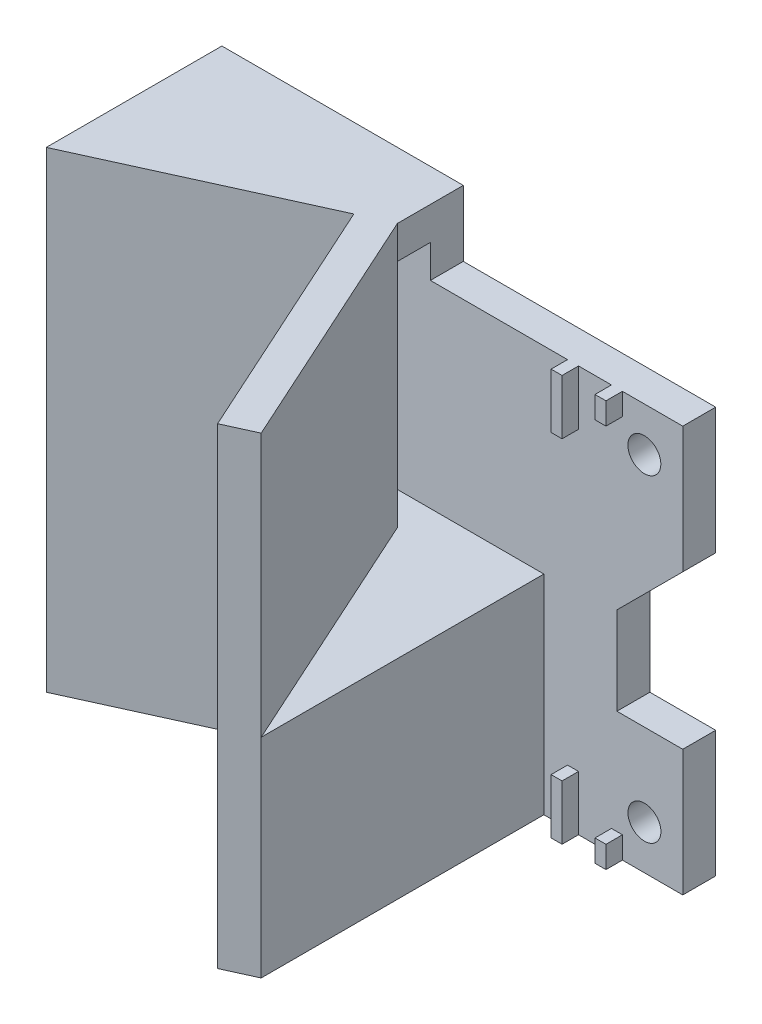
SolidWorks part; units mm, degrees
ref_plane "Alzado" through (0, 0, 0) normal (0, 0, 1) x (1, 0, 0)
ref_plane "Planta" through (0, 0, 0) normal (0, 1, 0) x (1, 0, 0)
ref_plane "Vista lateral" through (0, 0, 0) normal (1, 0, 0) x (0, 0, -1)
sketch "Croquis1" plane through (0, 0, 0) normal (0, 0, 1) x (1, 0, 0)
  line L0 (-56.1973, 24.9619) -> (-49.1973, 17.9619)
  line L1 (-52.1973, 33.4619) -> (-4.1973, 33.4619)
  line L2 (-56.1973, 29.4619) -> (-56.1973, 0.4619)
  line L3 (-52.4067, -3.5381) -> (-4.1973, -3.5381)
  line L4 (-4.1973, 33.4619) -> (-4.1973, -3.5381)
  line L5 (-56.1973, 24.9619) -> (-49.1973, 24.9619)
  line L6 (-56.1973, 24.9619) -> (-56.1973, 4.9619)
  line L7 (-56.1973, 4.9619) -> (-49.1973, 4.9619)
  line L8 (-4.1973, 21.9619) -> (-10.1973, 15.9619)
  line L9 (-4.1973, 21.9619) -> (-10.1973, 21.9619)
  line L10 (-4.1973, 21.9619) -> (-4.1973, 7.9619)
  line L11 (-4.1973, 7.9619) -> (-10.1973, 7.9619)
  line L13 (-49.1973, 17.9619) -> (-49.1973, 4.9619)
  line L14 (-10.1973, 15.9619) -> (-10.1973, 7.9619)
  circle A0 centre (-52.1973, 29.4619) radius 1.5
  circle A1 centre (-7.6973, 29.4619) radius 1.5
  circle A2 centre (-52.1915, 0.4619) radius 1.5
  circle A3 centre (-7.6915, 0.4619) radius 1.5
  arc A4 (-56.1973, 29.4619) -> (-52.1973, 33.4619) centre (-52.1973, 29.4619) cw
  arc A5 (-52.4067, -3.5381) -> (-56.1973, 0.4619) centre (-52.1915, 0.4619) cw
  dimension "D3" = 4
  dimension "D5" = 44.5
  dimension "D6" = 4
  dimension "D7" = 29
  dimension "D1" = 8.5
  dimension "D2" = 20
  dimension "D4" = 4
  dimension "D8" = 4
  dimension "D9" = 44.5
  dimension "D10" = 7
  dimension "D11" = 11.5
  dimension "D12" = 6
  dimension "D13" = 14
  dimension "D14" = 48
extrude "Saliente-Extruir1" add sketch "Croquis1" along normal blind 3
sketch "Croquis3" plane through (0, 0, 3) normal (0, 0, 1) x (1, 0, 0)
  line L0 (-52.1973, 33.4619) -> (-4.1973, 33.4619) construction
  line L1 (-49.1973, 33.4619) -> (-27.1973, 33.4619)
  line L2 (-49.1973, 33.4619) -> (-49.1973, -3.5381)
  line L3 (-49.1973, -3.5381) -> (-27.1973, -3.5381)
  line L4 (-27.1973, 33.4619) -> (-27.1973, -3.5381)
  line L5 (-52.4067, -3.5381) -> (-4.1973, -3.5381) construction
  circle A0 centre (-52.1973, 29.4619) radius 1.5 construction
  dimension "D1" = 3
  dimension "D2" = 22
extrude "Saliente-Extruir2" add sketch "Croquis3" along normal blind 13
sketch "Croquis4" plane through (0, -3.5381, 0) normal (0, -1, 0) x (1, 0, 0)
  line L0 (-27.1973, 16) -> (-27.1973, 6.0021)
  line L1 (-27.1973, 16) -> (-27.1973, 3) construction
  line L2 (-27.1973, 16) -> (-49.1973, 16)
  line L7 (-27.1973, 6.0021) -> (-49.1973, 16)
  line L8 (-27.1973, 3) -> (-4.1973, 3) construction
  dimension "D1" = 3.0021
extrude "Cortar-Extruir1" cut sketch "Croquis4" against normal up to vertex
sketch "Croquis6" plane through (0, 33.4619, 0) normal (0, 1, 0) x (1, 0, 0)
  line L0 (-27.1973, -6.0021) -> (-49.1973, -16)
  line L1 (-49.1973, -16) -> (-49.1973, 0)
  line L2 (-52.1973, 0) -> (-4.1973, 0) construction
  line L3 (-49.1973, 0) -> (-27.1973, 0)
  line L4 (-27.1973, 0) -> (-27.1973, -6.0021)
extrude "Saliente-Extruir4" add sketch "Croquis6" along normal blind 6
sketch "Croquis7" plane through (-27.1973, 0, 0) normal (1, 0, 0) x (0, 0, -1)
  line L0 (-6.0021, 39.4619) -> (-6.0021, -3.5381) construction
  line L1 (-6.0021, 15.4619) -> (-3, 15.4619)
  line L2 (-6.0021, 15.4619) -> (-6.0021, 36.4619)
  line L3 (-6.0021, 36.4619) -> (-3, 36.4619)
  line L4 (-3, 15.4619) -> (-3, 36.4619)
  line L5 (-6.0021, -3.5381) -> (-3, -3.5381) construction
  line L6 (-6.0021, 39.4619) -> (0, 39.4619) construction
  dimension "D1" = 19
  dimension "D2" = 3
extrude "Cortar-Extruir2" cut sketch "Croquis7" against normal up to vertex (22 mm away)
sketch "Croquis8" plane through (-2.3947, 0, -5.2695) normal (0.4137, 0, 0.9104) x (0.9104, 0, -0.4137)
  line L0 (-51.4089, 39.4619) -> (-27.2436, 39.4619) construction
  line L1 (-27.2436, -3.5381) -> (-30.2436, -3.5381)
  line L2 (-27.2436, -3.5381) -> (-27.2436, 39.4619)
  line L3 (-27.2436, 39.4619) -> (-30.2436, 39.4619)
  line L4 (-30.2436, -3.5381) -> (-30.2436, 39.4619)
  dimension "D1" = 3
extrude "Saliente-Extruir5" add sketch "Croquis8" along normal blind 25
sketch "Croquis9" plane through (0, -3.5381, 0) normal (0, -1, 0) x (1, 0, 0)
  line L0 (-16.854, 28.762) -> (-27.1973, 6.0021)
  line L1 (-27.1973, 6.0021) -> (-27.1973, 3)
  line L2 (-27.1973, 3) -> (-16.854, 3)
  line L3 (-27.1973, 3) -> (-4.1973, 3) construction
  line L4 (-16.854, 3) -> (-16.854, 28.762)
extrude "Saliente-Extruir6" add sketch "Croquis9" against normal up to vertex
sketch "Croquis13" plane through (0, 0, 3) normal (0, 0, 1) x (1, 0, 0)
  line L0 (-16.854, -3.5381) -> (-4.1973, -3.5381) construction
  line L1 (-10.6973, -3.5381) -> (-9.6973, -3.5381)
  line L2 (-10.6973, -3.5381) -> (-10.6973, -1.5381)
  line L3 (-10.6973, -1.5381) -> (-9.6973, -1.5381)
  line L4 (-9.6973, -3.5381) -> (-9.6973, -1.5381)
  line L5 (-4.1973, 7.9619) -> (-4.1973, -3.5381) construction
  line L6 (-10.6973, 31.4619) -> (-9.6973, 31.4619)
  line L7 (-10.6973, 31.4619) -> (-10.6973, 33.4619)
  line L8 (-10.6973, 33.4619) -> (-9.6973, 33.4619)
  line L9 (-9.6973, 31.4619) -> (-9.6973, 33.4619)
  line L10 (-13.6973, 28.4619) -> (-14.6973, 28.4619)
  line L11 (-13.6973, -3.5381) -> (-14.6973, -3.5381)
  line L12 (-13.6973, -3.5381) -> (-13.6973, 1.4619)
  line L13 (-13.6973, 1.4619) -> (-14.6973, 1.4619)
  line L14 (-14.6973, -3.5381) -> (-14.6973, 1.4619)
  line L15 (-13.6973, 28.4619) -> (-13.6973, 33.4619)
  line L16 (-13.6973, 33.4619) -> (-14.6973, 33.4619)
  line L17 (-14.6973, 28.4619) -> (-14.6973, 33.4619)
  dimension "D1" = 5.5
  dimension "D2" = 1
  dimension "D3" = 2
  dimension "D5" = 5
  dimension "D6" = 1
  dimension "D7" = 3
  dimension "D4" = 2
  dimension "D8" = 2
extrude "Saliente-Extruir8" add sketch "Croquis13" along normal blind 1.5
